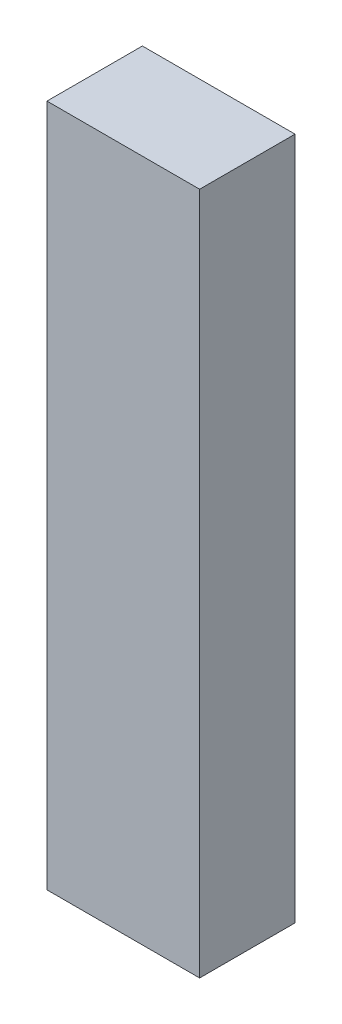
SolidWorks part; units mm, degrees
ref_plane "Front Plane" through (0, 0, 0) normal (0, 0, 1) x (1, 0, 0)
ref_plane "Top Plane" through (0, 0, 0) normal (0, 1, 0) x (1, 0, 0)
ref_plane "Right Plane" through (0, 0, 0) normal (1, 0, 0) x (0, 0, -1)
other "Configuration Table"
sketch "Sketch1" plane through (0, 0, 0) normal (0, 0, 1) x (1, 0, 0)
  line L1 (1298, 1469) -> (1338, 1469)
  line L2 (1298, 1469) -> (1298, 1648)
  line L3 (1298, 1648) -> (1338, 1648)
  line L4 (1338, 1469) -> (1338, 1648)
extrude "DET2_kablo_kanali_40x25_1" add sketch "Sketch1" against normal blind 25 from offset 775 separate body
